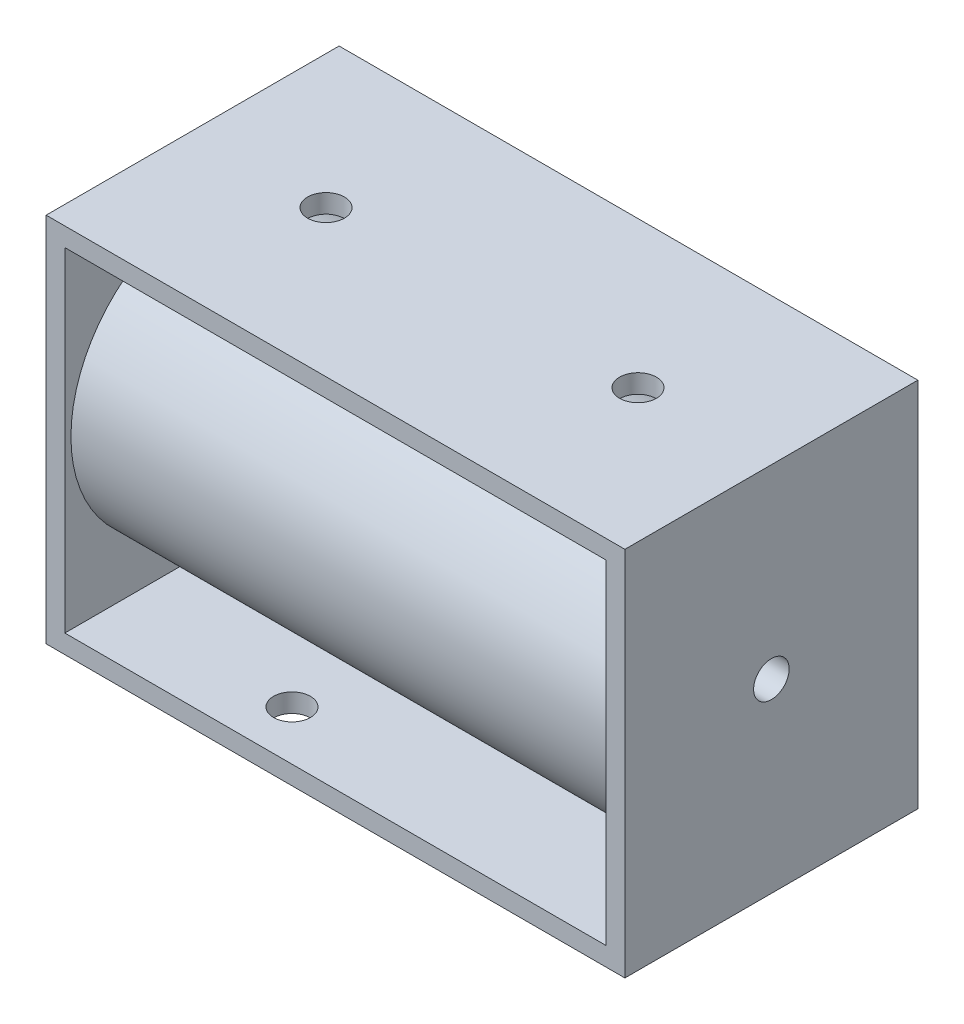
SolidWorks part; units mm, degrees
ref_plane "Front Plane" through (0, 0, 0) normal (0, 0, 1) x (1, 0, 0)
ref_plane "Top Plane" through (0, 0, 0) normal (0, 1, 0) x (1, 0, 0)
ref_plane "Right Plane" through (0, 0, 0) normal (1, 0, 0) x (0, 0, -1)
sketch "Sketch1" plane through (0, 0, 0) normal (0, 0, 1) x (1, 0, 0)
  line L1 (0, 0) -> (47.117, 0)
  line L2 (0, 0) -> (0, 30.226)
  line L3 (0, 30.226) -> (47.117, 30.226)
  line L4 (47.117, 0) -> (47.117, 30.226)
  dimension "D1" = 47.117
  dimension "D2" = 30.226
extrude "Boss-Extrude1" add sketch "Sketch1" along normal blind 23.8506
sketch "Sketch2" plane through (47.117, 0, 0) normal (1, 0, 0) x (0, 0, -1)
  line L0 (-11.9253, 30.226) -> (-11.9253, 0) construction
  line L1 (-23.8506, 30.226) -> (0, 30.226) construction
  line L2 (-23.8506, 0) -> (0, 0) construction
  circle A0 centre (-11.9253, 15.113) radius 1.4478
  dimension "D1" = 2.8956
sketch "Sketch3" plane through (0, 30.226, 0) normal (0, 1, 0) x (1, 0, 0)
  line L0 (0, -11.9253) -> (47.117, -11.9253) construction
  line L1 (0, -23.8506) -> (0, 0) construction
  line L2 (47.117, -23.8506) -> (47.117, 0) construction
  line L3 (23.5585, 0) -> (23.5585, -23.8506) construction
  line L4 (47.117, 0) -> (0, 0) construction
  line L5 (47.117, -23.8506) -> (0, -23.8506) construction
  circle A0 centre (10.8585, -11.9253) radius 1.4986
  circle A3 centre (36.2585, -11.9253) radius 1.4986
  dimension "D2" = 2.9972
  dimension "D1" = 12.7
sketch "Sketch4" plane through (0, 0, 23.8506) normal (0, 0, 1) x (1, 0, 0)
  line L0 (0, 15.113) -> (47.117, 15.113) construction
  line L1 (0, 30.226) -> (0, 0) construction
  line L2 (47.117, 0) -> (47.117, 30.226) construction
  line L3 (23.5585, 30.226) -> (23.5585, 0) construction
  line L4 (47.117, 30.226) -> (0, 30.226) construction
  line L5 (0, 0) -> (47.117, 0) construction
  line L7 (1.524, 28.702) -> (45.593, 28.702)
  line L8 (1.524, 28.702) -> (1.524, 1.524)
  line L9 (1.524, 1.524) -> (45.593, 1.524)
  line L10 (45.593, 28.702) -> (45.593, 1.524)
  line L11 (1.524, 28.702) -> (45.593, 1.524) construction
  line L12 (1.524, 1.524) -> (45.593, 28.702) construction
  point P12 (23.5585, 15.113)
  dimension "D1" = 1.524
  dimension "D2" = 1.524
extrude "Cut-Extrude1" cut sketch "Sketch4" against normal through all
sketch "Sketch5" plane through (1.524, 0, 0) normal (1, 0, 0) x (0, 0, -1)
  line L0 (-11.9253, 30.226) -> (-11.9253, 0) construction
  line L1 (-23.8506, 30.226) -> (0, 30.226) construction
  line L2 (-23.8506, 0) -> (0, 0) construction
  line L3 (-23.8506, 15.113) -> (0, 15.113) construction
  line L4 (-23.8506, 0) -> (-23.8506, 30.226) construction
  line L5 (0, 0) -> (0, 30.226) construction
  circle A0 centre (-11.9253, 15.113) radius 11.43
  dimension "D1" = 22.86
extrude "Boss-Extrude3" add sketch "Sketch5" along normal up to surface (44.069 mm away) up to face at (45.593, 15.113, 11.9253)
extrude "Cut-Extrude2" cut sketch "Sketch3" against normal blind 2.54
sketch "Sketch6" plane through (0, 0, 0) normal (0, -1, 0) x (1, 0, 0)
  line L0 (0, 23.8506) -> (0, 0) construction
  line L1 (0, 0) -> (47.117, 0) construction
  line L3 (0, 23.8506) -> (47.117, 23.8506) construction
  circle A0 centre (15.9766, 19.812) radius 1.4986
  circle A1 centre (10.8585, 11.9253) radius 1.4986
  circle A2 centre (36.5506, 4.0386) radius 1.4986
  point P12 (15.9766, 21.3106)
  point P13 (36.5506, 2.54)
  point P14 (14.478, 19.812)
  point P15 (35.052, 4.0386)
  dimension "D3" = 2.9972
  dimension "D1" = 10.8585
  dimension "D2" = 11.9253
  dimension "D4" = 2.54
  dimension "D5" = 2.54
  dimension "D6" = 14.478
  dimension "D7" = 35.052
extrude "Cut-Extrude3" cut sketch "Sketch6" against normal blind 2.54
extrude "Cut-Extrude4" cut sketch "Sketch2" against normal through all
sketch "Sketch7" plane through (0, 0, 0) normal (-1, 0, 0) x (0, 0, 1)
  circle A0 centre (11.9253, 15.113) radius 4.1783
  dimension "D1" = 8.3566
extrude "Cut-Extrude5" cut sketch "Sketch7" against normal blind 32.1564
chamfer "Chamfer1" distance 4.064 angle 30 1 edges at (32.1564, 15.113, 16.1036)
